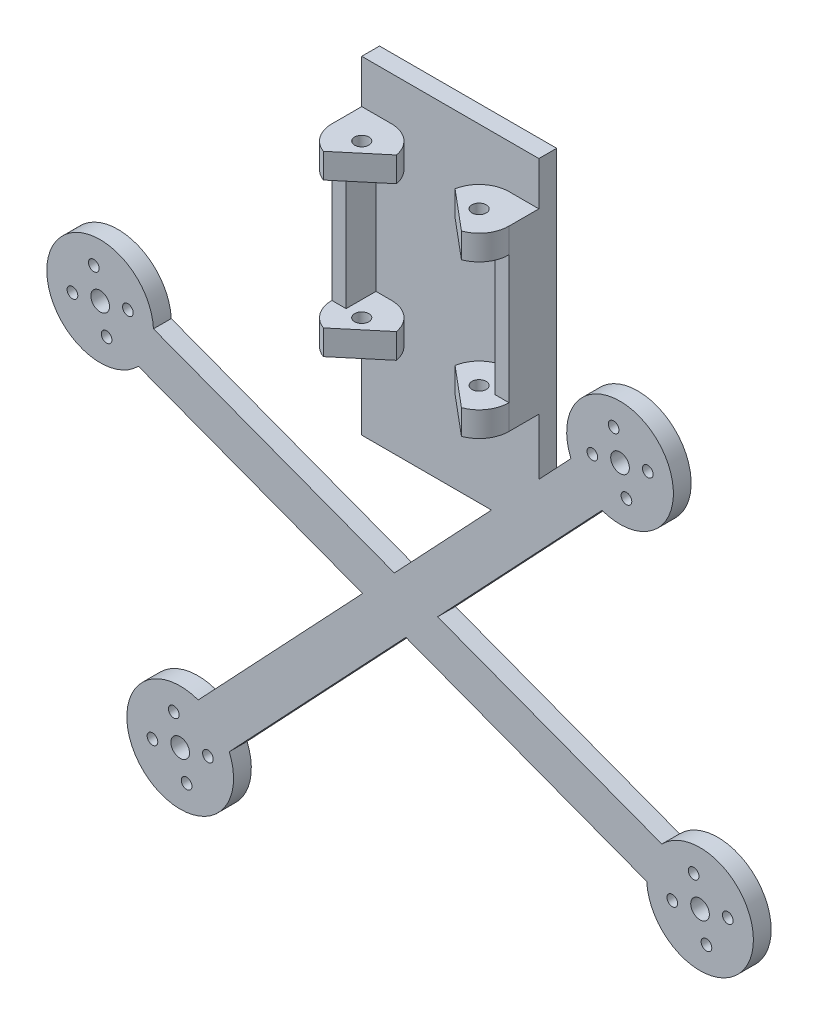
SolidWorks part; units mm, degrees
ref_plane "Front Plane" through (0, 0, 0) normal (0, 0, 1) x (1, 0, 0)
ref_plane "Top Plane" through (0, 0, 0) normal (0, 1, 0) x (1, 0, 0)
ref_plane "Right Plane" through (0, 0, 0) normal (1, 0, 0) x (0, 0, -1)
sketch "Sketch1" plane through (0, 0, 0) normal (0, 1, 0) x (1, 0, 0)
  line L0 (0, 22.8391) -> (0, -19.8342) construction
  line L1 (-35.1495, 0) -> (37.3645, 0) construction
  line L2 (-24.9, 0) -> (-24.9, 13.4)
  line L3 (-24.9, 13.4) -> (24.9, 13.4)
  line L4 (24.9, 0) -> (24.9, 13.4)
  line L5 (-19.4124, -7.879) -> (-8.235, 1.5)
  line L6 (19.4124, -7.879) -> (8.235, 1.5)
  line L7 (16.5, 8.4) -> (-16.5, 8.4)
  arc A0 (19.4124, -7.879) -> (24.9, 0) centre (16.5, 0) ccw
  arc A1 (-19.4124, -7.879) -> (-24.9, 0) centre (-16.5, 0) cw
  arc A2 (-16.5, 8.4) -> (-8.235, 1.5) centre (-16.5, 0) cw
  arc A3 (16.5, 8.4) -> (8.235, 1.5) centre (16.5, 0) ccw
  circle A4 centre (-16.5, 0) radius 8.4 construction
  circle A5 centre (16.5, 0) radius 8.4 construction
  point P14 (0, 13.4)
  dimension "D1" = 16.8
  dimension "D2" = 33
  dimension "D3" = 5
  dimension "D4" = 130
  dimension "D5" = 1.5
  dimension "D6" = 13.4
extrude "Boss-Extrude2" add sketch "Sketch1" along normal blind 7
sketch "Sketch3" plane through (0, 7, 0) normal (0, 1, 0) x (1, 0, 0)
  circle A0 centre (-16.5, 0) radius 2
  circle A1 centre (16.5, 0) radius 2
  dimension "D1" = 4
extrude "Cut-Extrude2" cut sketch "Sketch3" against normal through all both and the other way through all
sketch "Sketch4" plane through (0, 7, 0) normal (0, 1, 0) x (1, 0, 0)
  line L0 (-24.9, 13.4) -> (-24.9, 0)
  line L1 (-24.9, 13.4) -> (24.9, 13.4)
  line L2 (24.9, 13.4) -> (24.9, 0)
  line L3 (0, 13.4) -> (0, 0) construction
  line L4 (-16.5, 8.4) -> (16.5, 8.4)
  line L5 (-16.5, 8.4) -> (16.5, 8.4) construction
  line L6 (16.5, 8.4) -> (20.9, 8.4)
  line L7 (20.9, 8.4) -> (20.9, 0)
  line L8 (20.9, 0) -> (24.9, 0)
  line L9 (-20.9, 0) -> (-24.9, 0)
  line L10 (-20.9, 8.4) -> (-20.9, 0)
  line L11 (-16.5, 8.4) -> (-20.9, 8.4)
  circle A0 centre (-16.5, 0) radius 3.7 construction
  point P21 (0, 8.4)
  dimension "D2" = 7.4
  dimension "D1" = 4
extrude "Boss-Extrude3" add sketch "Sketch4" along normal blind 36
sketch "Sketch5" plane through (0, 43, 0) normal (0, 1, 0) x (1, 0, 0)
  line L12 (-24.9, 13.4) -> (-24.9, 0)
  line L13 (24.9, 13.4) -> (-24.9, 13.4)
  line L14 (24.9, 0) -> (24.9, 13.4)
  line L15 (8.235, 1.5) -> (19.4124, -7.879)
  line L16 (-16.5, 8.4) -> (16.5, 8.4)
  line L17 (-19.4124, -7.879) -> (-8.235, 1.5)
  line L18 (-24.9, 13.4) -> (-24.9, 0)
  line L19 (24.9, 13.4) -> (-24.9, 13.4)
  line L20 (24.9, 0) -> (24.9, 13.4)
  line L21 (8.235, 1.5) -> (19.4124, -7.879)
  line L22 (-16.5, 8.4) -> (16.5, 8.4)
  line L23 (-19.4124, -7.879) -> (-8.235, 1.5)
  circle A0 centre (-16.5, 0) radius 2 construction
  circle A1 centre (16.5, 0) radius 2
  circle A2 centre (16.5, 0) radius 2 construction
  circle A4 centre (-16.5, 0) radius 2
  arc A8 (-24.9, 0) -> (-19.4124, -7.879) centre (-16.5, 0) ccw
  arc A9 (19.4124, -7.879) -> (24.9, 0) centre (16.5, 0) ccw
  arc A10 (16.5, 8.4) -> (8.235, 1.5) centre (16.5, 0) ccw
  arc A11 (-8.235, 1.5) -> (-16.5, 8.4) centre (-16.5, 0) ccw
  arc A12 (-24.9, 0) -> (-19.4124, -7.879) centre (-16.5, 0) ccw
  arc A13 (19.4124, -7.879) -> (24.9, 0) centre (16.5, 0) ccw
  arc A14 (16.5, 8.4) -> (8.235, 1.5) centre (16.5, 0) ccw
  arc A15 (-8.235, 1.5) -> (-16.5, 8.4) centre (-16.5, 0) ccw
  dimension "D1" = 0
extrude "Boss-Extrude4" add sketch "Sketch5" along normal blind 7
sketch "Sketch13" plane through (0, 50, 0) normal (0, 1, 0) x (1, 0, 0)
  line L0 (24.9, 0) -> (24.9, 13.4) construction
  line L5 (-24.9, 13.4) -> (24.9, 13.4)
  line L6 (-24.9, 13.4) -> (-24.9, 8.4)
  line L7 (-24.9, 8.4) -> (24.9, 8.4)
  line L8 (24.9, 13.4) -> (24.9, 8.4)
  line L9 (-16.5, 8.4) -> (16.5, 8.4) construction
extrude "Boss-Extrude6" add sketch "Sketch13" along normal blind 12.25
sketch "Sketch15" plane through (0, 0, 0) normal (0, -1, 0) x (1, 0, 0)
  line L0 (24.9, 0) -> (24.9, -13.4) construction
  line L1 (-24.9, -13.4) -> (24.9, -13.4)
  line L2 (-24.9, -13.4) -> (-24.9, -8.4)
  line L3 (-24.9, -8.4) -> (24.9, -8.4)
  line L4 (24.9, -13.4) -> (24.9, -8.4)
  line L5 (-16.5, -8.4) -> (16.5, -8.4) construction
extrude "Boss-Extrude7" add sketch "Sketch15" along normal blind 30
sketch "Sketch12" plane through (0, 0, -13.4) normal (0, 0, -1) x (-1, 0, 0)
  line L8 (-58.9662, -49.1287) -> (87.1893, -82.8713) construction
  line L9 (-24.9, -30) -> (24.9, -30) construction
  line L10 (24.9, -30) -> (24.9, -41.4972) construction
  line L19 (24.9, -41.4972) -> (-24.9, -30) construction
  line L20 (24.9, -41.4972) -> (7.6028, -116.4198) construction
  line L21 (18.9834, -67.1248) -> (14.1116, -66) construction
  line L22 (98.4369, -34.1528) -> (-47.7186, -0.4102) construction
  line L23 (98.4369, -34.1528) -> (75.9418, -131.5898) construction
  line L24 (75.9418, -131.5898) -> (-70.2137, -97.8472) construction
  line L25 (-47.7186, -0.4102) -> (-70.2137, -97.8472) construction
  line L26 (98.4369, -34.1528) -> (-70.2137, -97.8472) construction
  line L27 (75.9418, -131.5898) -> (-47.7186, -0.4102) construction
  line L28 (14.1116, -66) -> (2.864, -114.7185) construction
  line L29 (3.5721, -63.5668) -> (-59.4725, -87.3769)
  line L30 (12.4894, -73.0263) -> (-55.2328, -98.603)
  line L31 (3.5721, -63.5668) -> (-42.6544, -14.5294)
  line L32 (15.7337, -58.9737) -> (-33.9225, -6.2981)
  line L33 (15.7337, -58.9737) -> (83.4559, -33.397)
  line L34 (24.651, -68.4332) -> (87.6957, -44.6231)
  line L35 (12.4894, -73.0263) -> (62.1457, -125.7019)
  line L36 (24.651, -68.4332) -> (70.8775, -117.4706)
  arc A0 (-33.9225, -6.2981) -> (-42.6544, -14.5294) centre (-47.7186, -0.4102) ccw
  circle A1 centre (-47.7186, -0.4102) radius 8 construction
  circle A2 centre (-49.5182, -8.2051) radius 1.5
  circle A3 centre (-55.5136, 1.3894) radius 1.5
  circle A4 centre (-45.919, 7.3848) radius 1.5
  circle A5 centre (-39.9237, -2.2098) radius 1.5
  circle A6 centre (-62.4188, -99.6468) radius 1.5
  circle A7 centre (-72.0133, -105.6421) radius 1.5
  circle A8 centre (-68.4141, -90.0522) radius 1.5
  circle A9 centre (-78.0087, -96.0476) radius 1.5
  arc A10 (-55.2328, -98.603) -> (-59.4725, -87.3769) centre (-70.2137, -97.8472) cw
  arc A11 (83.4559, -33.397) -> (87.6957, -44.6231) centre (98.4369, -34.1528) cw
  circle A12 centre (100.2365, -26.3579) radius 1.5
  circle A13 centre (90.6419, -32.3532) radius 1.5
  circle A14 centre (96.6373, -41.9478) radius 1.5
  circle A15 centre (106.2318, -35.9524) radius 1.5
  circle A16 centre (68.1468, -129.7902) radius 1.5
  circle A17 centre (77.7414, -123.7949) radius 1.5
  circle A18 centre (83.7367, -133.3894) radius 1.5
  circle A19 centre (74.1422, -139.3848) radius 1.5
  arc A20 (62.1457, -125.7019) -> (70.8775, -117.4706) centre (75.9418, -131.5898) ccw
  circle A21 centre (-47.7186, -0.4102) radius 2.625
  circle A22 centre (-70.2137, -97.8472) radius 2.625
  circle A23 centre (98.4369, -34.1528) radius 2.625
  circle A24 centre (75.9418, -131.5898) radius 2.625
  point P28 (-47.7186, -0.4102)
  dimension "D7" = 30
  dimension "D8" = 16
  dimension "D9" = 3
  dimension "D12" = 5.25
  dimension "D1" = 13
  dimension "D2" = 5
  dimension "D3" = 66
  dimension "D4" = 150
  dimension "D5" = 100
  dimension "D6" = 13
  dimension "D11" = 12
  dimension "D10" = 4
extrude "Boss-Extrude8" add sketch "Sketch12" against normal blind 5
